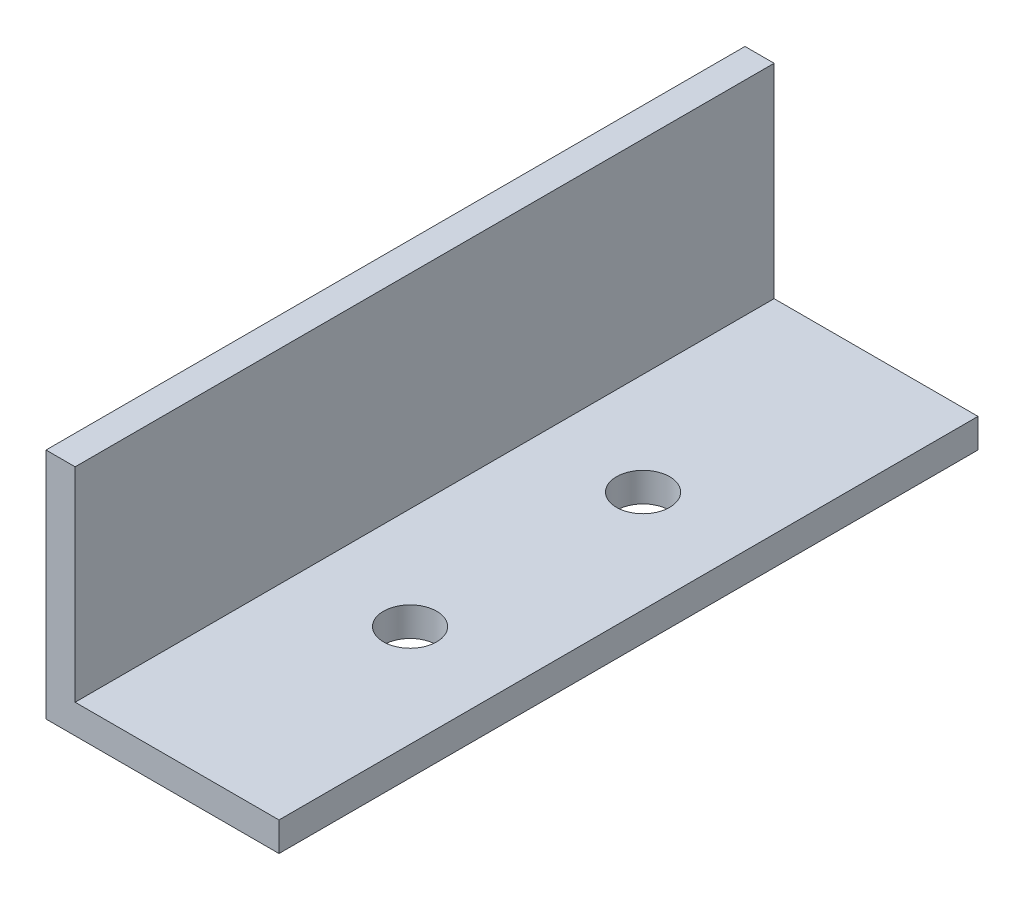
SolidWorks part; units mm, degrees
ref_plane "Front Plane" through (0, 0, 0) normal (0, 0, 1) x (1, 0, 0)
ref_plane "Top Plane" through (0, 0, 0) normal (0, 1, 0) x (1, 0, 0)
ref_plane "Right Plane" through (0, 0, 0) normal (1, 0, 0) x (0, 0, -1)
sketch "Sketch1" plane through (0, 0, 0) normal (0, 0, 1) x (1, 0, 0)
  line L0 (0, 0) -> (25.4, 0)
  line L1 (0, 0) -> (0, 25.4)
  line L2 (3.175, 3.175) -> (25.4, 3.175)
  line L3 (3.175, 3.175) -> (3.175, 25.4)
  line L4 (0, 25.4) -> (3.175, 25.4)
  line L5 (25.4, 0) -> (25.4, 3.175)
  dimension "D1" = 25.4
  dimension "D2" = 25.4
  dimension "D3" = 3.175
extrude "Boss-Extrude1" add sketch "Sketch1" along normal blind 76.2
sketch "Sketch2" plane through (0, 0, 0) normal (0, 1, 0) x (1, 0, 0)
  line L0 (14.2875, -76.2) -> (14.2875, 0) construction
  line L1 (25.4, -76.2) -> (3.175, -76.2) construction
  line L2 (25.4, 0) -> (3.175, 0) construction
  circle A0 centre (14.2875, -25.4) radius 2.9
  circle A1 centre (14.2875, -50.8) radius 2.9
  dimension "D1" = 5.8
  dimension "D3" = 5.8
  dimension "D2" = 25.4
  dimension "D4" = 25.4
extrude "Cut-Extrude1" cut sketch "Sketch2" along normal blind 76.2
